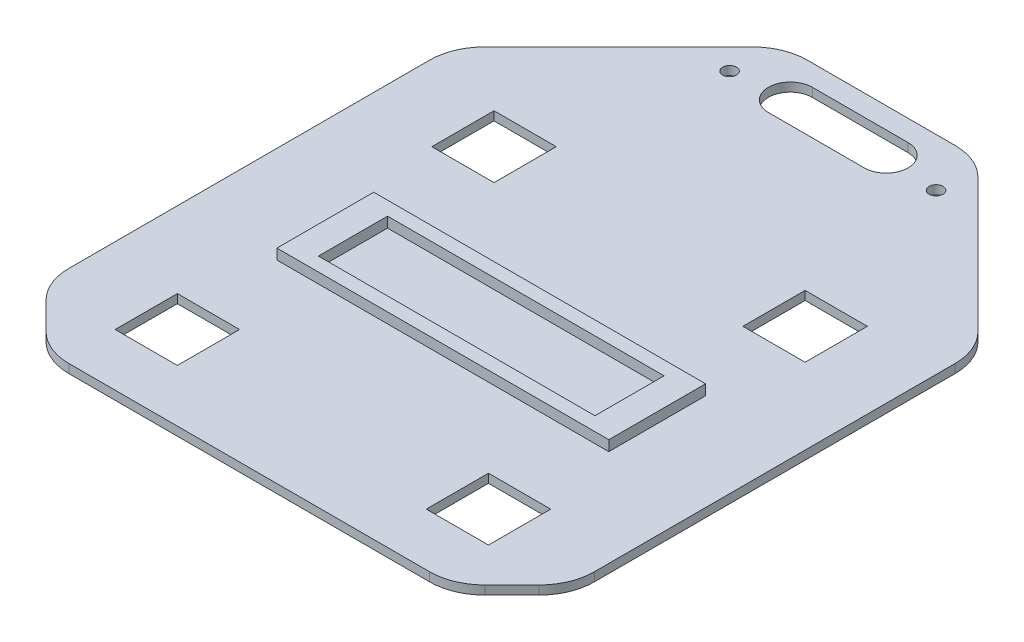
SolidWorks part; units mm, degrees
ref_plane "Front Plane" through (0, 0, 0) normal (0, 0, 1) x (1, 0, 0)
ref_plane "Top Plane" through (0, 0, 0) normal (0, 1, 0) x (1, 0, 0)
ref_plane "Right Plane" through (0, 0, 0) normal (1, 0, 0) x (0, 0, -1)
sketch "Sketch1" plane through (0, 0, 0) normal (0, 1, 0) x (1, 0, 0)
  line L0 (0, 0) -> (294, 0)
  line L1 (294, 0) -> (336.996, 43.004)
  line L2 (336.996, 43.004) -> (336.996, 337.004)
  line L3 (336.996, 337.004) -> (217, 457)
  line L4 (217, 457) -> (77, 457)
  line L5 (77, 457) -> (-42.996, 337.004)
  line L6 (-42.996, 337.004) -> (-42.996, 43.004)
  line L7 (-42.996, 43.004) -> (0, 0)
  dimension "D1" = 294
  dimension "D2" = 294
  dimension "D3" = 457
  dimension "D5" = 60.8112
  dimension "D7" = 169.7
  dimension "D9" = 225
  dimension "D10" = 140
extrude "Body" add sketch "Sketch1" along normal blind 6.35
sketch "Sketch2" plane through (0, 6.35, 0) normal (0, 1, 0) x (1, 0, 0)
  line L3 (217, 457) -> (77, 457) construction
  line L4 (112.35, 441.8) -> (181.65, 441.8)
  line L5 (112.35, 441.8) -> (112.35, 410.1)
  line L6 (112.35, 410.1) -> (181.65, 410.1)
  line L7 (181.65, 441.8) -> (181.65, 410.1)
  line L8 (217, 457) -> (77, 457)
  arc A1 (112.35, 441.8) -> (112.35, 410.1) centre (112.35, 425.95) ccw
  arc A2 (181.65, 441.8) -> (181.65, 410.1) centre (181.65, 425.95) cw
  point P8 (147, 410.1)
  point P9 (147, 457)
  dimension "D3" = 15.85
  dimension "D4" = 15.2
  dimension "D1" = 69.3
  dimension "D2" = 31.7
extrude "Handle" cut sketch "Sketch2" against normal blind 6.35 contours L6 A2 L4 A1
sketch "Sketch3" plane through (0, 6.35, 0) normal (0, 1, 0) x (1, 0, 0)
  line L0 (0, 0) -> (294, 0) construction
  line L4 (336.996, 43.004) -> (336.996, 337.004) construction
  line L5 (-42.996, 337.004) -> (-42.996, 43.004) construction
  circle A0 centre (27.004, 300) radius 10
  circle A1 centre (266.996, 300) radius 10
  circle A2 centre (266.996, 50) radius 10
  circle A3 centre (27.004, 50) radius 10
  dimension "D1" = 50
  dimension "D2" = 250
  dimension "D3" = 70
  dimension "D4" = 70
extrude "Bearing Rings" cut sketch "Sketch3" against normal blind 3.175 contours A3 | A2 | A1 | A0
sketch "Sketch7" plane through (0, 6.35, 0) normal (0, 1, 0) x (1, 0, 0)
  line L0 (-42.996, 337.004) -> (-42.996, 43.004) construction
  line L1 (27.004, 210) -> (266.996, 210)
  line L2 (27.004, 210) -> (27.004, 140)
  line L3 (27.004, 140) -> (266.996, 140)
  line L4 (266.996, 210) -> (266.996, 140)
  line L5 (0, 0) -> (294, 0) construction
  circle A0 centre (27.004, 50) radius 10 construction
  circle A1 centre (266.996, 50) radius 10 construction
  circle A2 centre (266.996, 300) radius 10 construction
  circle A3 centre (27.004, 300) radius 10 construction
  circle A4 centre (27.004, 50) radius 10
  circle A5 centre (266.996, 50) radius 10
  circle A6 centre (266.996, 300) radius 10
  circle A7 centre (27.004, 300) radius 10
  dimension "D1" = 70
  dimension "D2" = 70
  dimension "D3" = 239.992
  dimension "D4" = 140
extrude "Outside Perimeter Constraint" add sketch "Sketch7" along normal blind 7.5 contours L2 L3 L4 L1
sketch "Sketch10" plane through (0, 13.85, 0) normal (0, 1, 0) x (1, 0, 0)
  line L4 (266.996, 210) -> (27.004, 210)
  line L5 (27.004, 210) -> (27.004, 140)
  line L6 (27.004, 140) -> (266.996, 140)
  line L7 (266.996, 140) -> (266.996, 210)
  line L8 (266.996, 210) -> (27.004, 210)
  line L9 (27.004, 210) -> (27.004, 140)
  line L10 (27.004, 140) -> (266.996, 140)
  line L11 (266.996, 140) -> (266.996, 210)
  line L17 (47, 200) -> (247, 200)
  line L18 (47, 200) -> (47, 150)
  line L19 (47, 150) -> (247, 150)
  line L20 (247, 200) -> (247, 150)
  line L21 (0, 0) -> (294, 0) construction
  line L22 (-42.996, 337.004) -> (-42.996, 43.004) construction
  point P8 (147, 150)
  point P9 (147, 200)
  point P10 (147, 210)
  point P11 (47, 175)
  point P12 (247, 175)
  point P13 (266.996, 175)
  dimension "D2" = 50
  dimension "D3" = 200
  dimension "D4" = 150
  dimension "D5" = 140
  dimension "D6" = 70
  dimension "D1" = 0
extrude "Inside Perimeter Constraint" cut sketch "Sketch10" against normal blind 7.5 contours L18 L19 L20 L17
sketch "Sketch11" plane through (0, 6.35, 0) normal (0, 1, 0) x (1, 0, 0)
  line L0 (217, 457) -> (77, 457) construction
  circle A0 centre (221.65, 422) radius 5
  arc A1 (181.65, 410.1) -> (181.65, 441.8) centre (181.65, 425.95) ccw construction
  circle A2 centre (72.35, 422) radius 5
  arc A3 (112.35, 441.8) -> (112.35, 410.1) centre (112.35, 425.95) ccw construction
  dimension "D1" = 35
  dimension "D3" = 35
  dimension "D2" = 40
  dimension "D4" = 40
extrude "Locking Mechanism Holes" cut sketch "Sketch11" against normal blind 6.36 contours A0 | A2
sketch "Sketch12" plane through (0, 6.35, 0) normal (0, 1, 0) x (1, 0, 0)
  line L0 (-42.996, 337.004) -> (-42.996, 43.004) construction
  line L1 (12.004, 312) -> (57.004, 312)
  line L2 (12.004, 312) -> (12.004, 267)
  line L3 (12.004, 267) -> (57.004, 267)
  line L4 (57.004, 312) -> (57.004, 267)
  line L5 (217, 457) -> (77, 457) construction
  line L6 (336.996, 43.004) -> (336.996, 337.004) construction
  line L7 (281.996, 312) -> (236.996, 312)
  line L8 (281.996, 312) -> (281.996, 267)
  line L9 (281.996, 267) -> (236.996, 267)
  line L10 (236.996, 312) -> (236.996, 267)
  line L11 (47, 200) -> (47, 150) construction
  line L16 (47, 200) -> (47, 150) construction
  line L17 (247, 200) -> (247, 150) construction
  line L18 (247, 200) -> (247, 150) construction
  line L19 (47, 175) -> (247, 175) construction
  line L20 (281.996, 83) -> (236.996, 83)
  line L21 (236.996, 38) -> (236.996, 83)
  line L22 (281.996, 38) -> (236.996, 38)
  line L23 (281.996, 38) -> (281.996, 83)
  line L24 (12.004, 83) -> (57.004, 83)
  line L25 (57.004, 38) -> (57.004, 83)
  line L26 (12.004, 38) -> (57.004, 38)
  line L27 (12.004, 38) -> (12.004, 83)
  line L31 (47, 150) -> (247, 150) construction
  line L32 (0, 0) -> (294, 0) construction
  dimension "D2" = 112
  dimension "D1" = 45
  dimension "D3" = 55
  dimension "D4" = 145
  dimension "D5" = 150
  dimension "D7" = 145
  dimension "D8" = 55
extrude "Square Bearing Cut" cut sketch "Sketch12" against normal blind 6.35 contours L8 L9 L10 L7 | L4 L3 L2 L1 | L25 L24 L27 L26 | L23 L20 L21 L22
fillet "Fillet1" radius 40 2 edges at (217, 3.175, -457) (77, 3.175, -457)
fillet "Fillet2" radius 40 6 edges at (-42.996, 3.175, -337.004) (-42.996, 3.175, -43.004) (0, 3.175, 0) (294, 3.175, 0) (336.996, 3.175, -43.004) (336.996, 3.175, -337.004)
